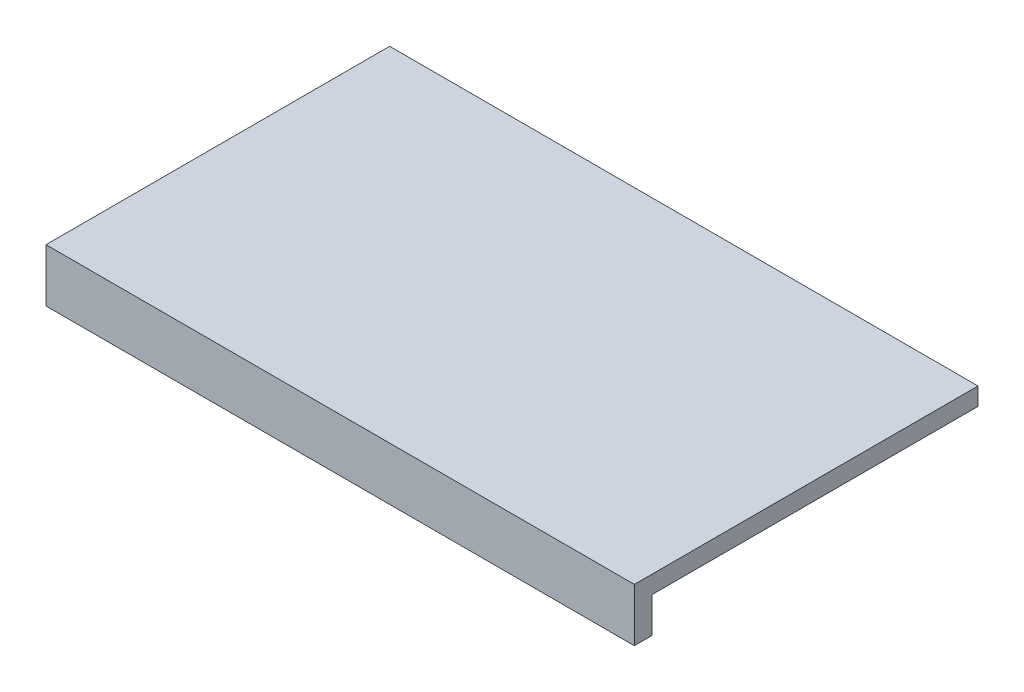
SolidWorks part; units mm, degrees
ref_plane "Front Plane" through (0, 0, 0) normal (0, 0, 1) x (1, 0, 0)
ref_plane "Top Plane" through (0, 0, 0) normal (0, 1, 0) x (1, 0, 0)
ref_plane "Right Plane" through (0, 0, 0) normal (1, 0, 0) x (0, 0, -1)
sketch "Sketch1" plane through (0, 0, 0) normal (0, 1, 0) x (1, 0, 0)
  line L1 (-282.5, -165) -> (282.5, -165)
  line L2 (-282.5, -165) -> (-282.5, 165)
  line L3 (-282.5, 165) -> (282.5, 165)
  line L4 (282.5, -165) -> (282.5, 165)
  line L5 (-282.5, -165) -> (282.5, 165) construction
  line L6 (-282.5, 165) -> (282.5, -165) construction
  point P0 (0, 0)
  dimension "D1" = 330
  dimension "D2" = 565
extrude "Boss-Extrude1" add sketch "Sketch1" along normal blind 17
sketch "Sketch2" plane through (0, 0, 0) normal (0, -1, 0) x (1, 0, 0)
  line L0 (282.5, 165) -> (282.5, -165) construction
  line L1 (-282.5, 165) -> (282.5, 165)
  line L2 (-282.5, 165) -> (-282.5, 148)
  line L3 (-282.5, 148) -> (282.5, 148)
  line L4 (282.5, 165) -> (282.5, 148)
  dimension "D1" = 17
extrude "Boss-Extrude2" add sketch "Sketch2" along normal blind 34
